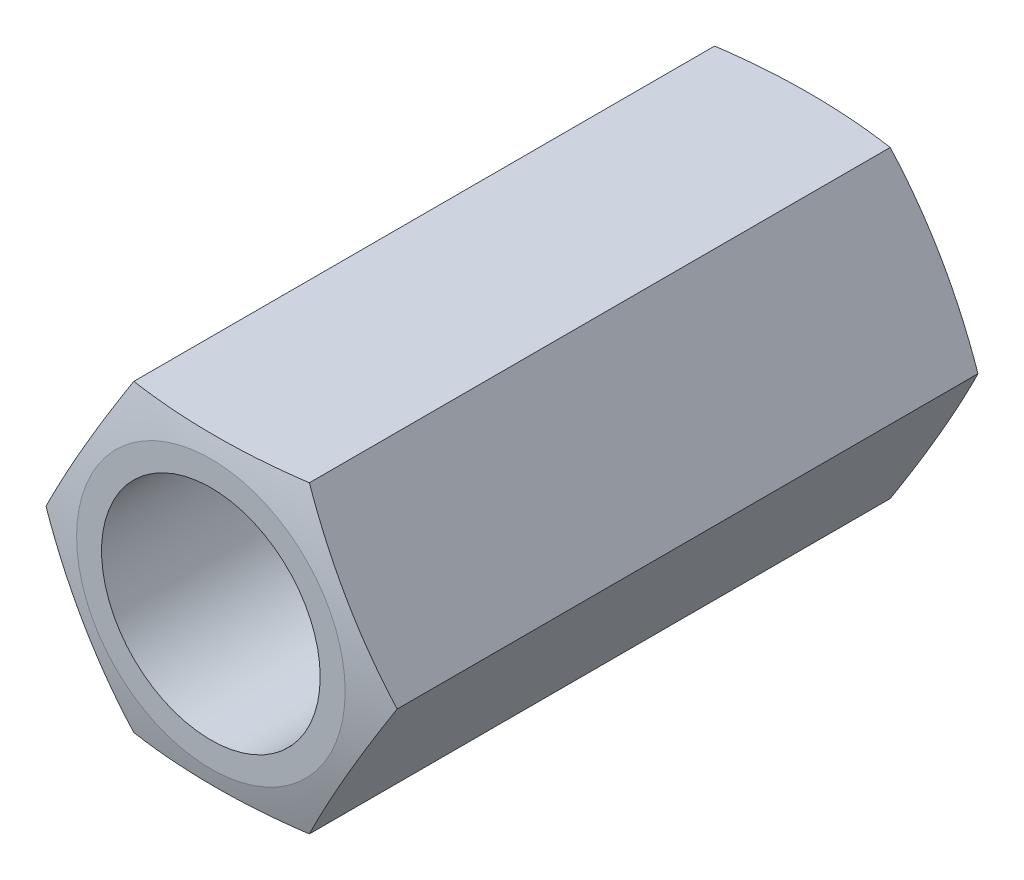
SolidWorks part; units mm, degrees
ref_plane "Front Plane" through (0, 0, 0) normal (0, 0, 1) x (1, 0, 0)
ref_plane "Top Plane" through (0, 0, 0) normal (0, 1, 0) x (1, 0, 0)
ref_plane "Right Plane" through (0, 0, 0) normal (1, 0, 0) x (0, 0, -1)
sketch "Sketch1" plane through (0, 0, 0) normal (0, 0, 1) x (1, 0, 0)
  line L1 (7.4057, 0) -> (3.7028, 6.4135)
  line L2 (3.7028, 6.4135) -> (-3.7028, 6.4135)
  line L3 (-3.7028, 6.4135) -> (-7.4057, 0)
  line L4 (-7.4057, 0) -> (-3.7028, -6.4135)
  line L5 (-3.7028, -6.4135) -> (3.7028, -6.4135)
  line L6 (3.7028, -6.4135) -> (7.4057, 0)
  circle A0 centre (0, 0) radius 6.4135 construction
  circle A1 centre (0, 0) radius 3.8989
  dimension "D1" = 12.827
  dimension "D2" = 7.7978
extrude "Boss-Extrude1" add sketch "Sketch1" along normal blind 25.4
sketch "Sketch2" plane through (0, 0, 25.4) normal (0, 0, 1) x (1, 0, 0)
  circle A0 centre (0, 0) radius 4.6101
  dimension "D1" = 9.2202
extrude "Cut-Extrude1" cut sketch "Sketch2" against normal blind 15.875
sketch "Sketch3" plane through (0, 0, 0) normal (1, 0, 0) x (0, 0, -1)
  line L0 (-25.4, 0) -> (0, 0) construction
  line L1 (0.6236, 0) -> (5.6581, 0)
  line L3 (-21.8877, 0) -> (49978.1123, 0) construction
  line L4 (3.7816, 10.6319) -> (-1.6473, 10.6319)
  line L5 (-23.7527, 10.6319) -> (-29.1816, 10.6319)
  line L6 (-31.0581, 0) -> (-26.0236, 0)
  arc A0 (0.6236, 0) -> (-1.6473, 10.6319) centre (-25.4, 0) ccw
  arc A1 (5.6581, 0) -> (3.7816, 10.6319) centre (-25.4, 0) ccw
  arc A6 (-23.7527, 10.6319) -> (-26.0236, 0) centre (0, 0) ccw
  arc A7 (-29.1816, 10.6319) -> (-31.0581, 0) centre (0, 0) ccw
revolve "Cut-Revolve1" cut sketch "Sketch3" angle 360 about L3
